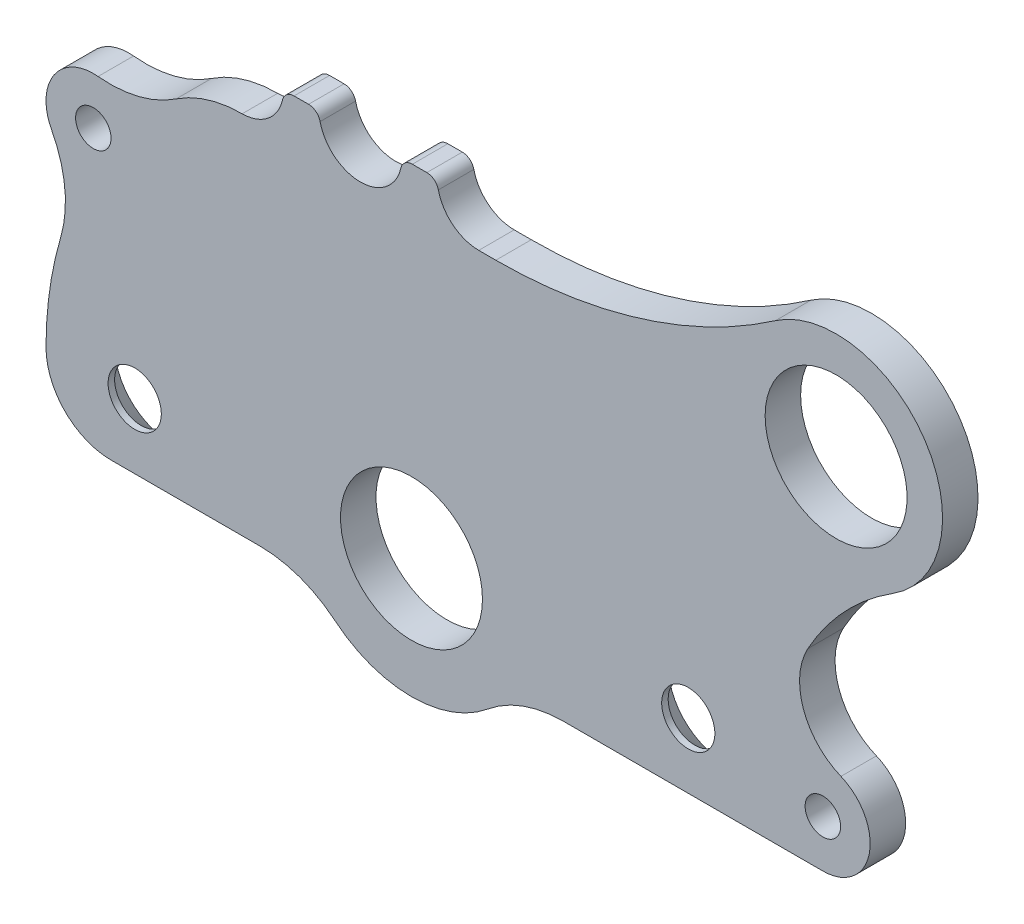
SolidWorks part; units mm, degrees
ref_plane "Front Plane" through (0, 0, 0) normal (0, 0, 1) x (1, 0, 0)
ref_plane "Top Plane" through (0, 0, 0) normal (0, 1, 0) x (1, 0, 0)
ref_plane "Right Plane" through (0, 0, 0) normal (1, 0, 0) x (0, 0, -1)
sketch "Sketch1" plane through (0, 0, 0) normal (0, 0, 1) x (1, 0, 0)
  line L0 (-25.4, 0) -> (25.4, 0) construction
  line L1 (-25.4, 2.5) -> (25.4, 2.5) construction
  line L2 (-25.4, -2.5) -> (25.4, -2.5) construction
  line L3 (-25.4, 0) -> (-21.4, 0) construction
  line L6 (-25.4, 2.5) -> (-21.4, 2.5) construction
  line L7 (-25.4, -2.5) -> (-21.4, -2.5) construction
  line L8 (0, 0) -> (0, -25.4) construction
  line L9 (25.4, 0) -> (21.4, 0) construction
  line L10 (25.4, 2.5) -> (21.4, 2.5) construction
  line L11 (25.4, -2.5) -> (21.4, -2.5) construction
  line L12 (-25.4, 0) -> (25.4, 0) construction
  line L13 (-25.4, 5.5) -> (25.4, 5.5) construction
  line L14 (-25.4, -5.5) -> (25.4, -5.5) construction
  line L17 (-25.4, -5.5) -> (-12.8349, -5.5)
  line L18 (12.8349, -5.5) -> (25.4, -5.5)
  circle A0 centre (0, 0) radius 25.4 construction
  circle A1 centre (0, 0) radius 6.35 construction
  arc A2 (-25.4, 2.5) -> (-25.4, -2.5) centre (-25.4, 0) ccw construction
  arc A3 (25.4, -2.5) -> (25.4, 2.5) centre (25.4, 0) ccw construction
  arc A6 (-25.4, 2.5) -> (-25.4, -2.5) centre (-25.4, 0) ccw construction
  arc A7 (-21.4, -2.5) -> (-21.4, 2.5) centre (-21.4, 0) ccw construction
  arc A8 (25.4, 2.5) -> (25.4, -2.5) centre (25.4, 0) cw construction
  arc A9 (21.4, -2.5) -> (21.4, 2.5) centre (21.4, 0) cw construction
  arc A10 (-25.4, 5.5) -> (-25.4, -5.5) centre (-25.4, 0) ccw construction
  arc A11 (25.4, -5.5) -> (25.4, 5.5) centre (25.4, 0) ccw construction
  arc A12 (-30.9, 0) -> (30.9, 0) centre (0, 0) cw
  arc A14 (-30.9, 0) -> (-25.4, -5.5) centre (-25.4, 0) ccw
  arc A15 (30.9, 0) -> (25.4, -5.5) centre (25.4, 0) cw
  arc A16 (-6.4571, -7.7978) -> (6.4571, -7.7978) centre (0, 0) ccw
  arc A17 (12.8349, -5.5) -> (6.4571, -7.7978) centre (12.8349, -15.5) ccw
  arc A18 (-12.8349, -5.5) -> (-6.4571, -7.7978) centre (-12.8349, -15.5) cw
  circle A19 centre (0, 0) radius 6
  point P6 (0, 0)
  point P13 (-23.4, 0)
  point P21 (23.4, 0)
  point P28 (0, 0)
  point P43 (8.5, -5.5)
  point P47 (-8.5, -5.5)
  dimension "D1" = 50.8
  dimension "D2" = 12.7
  dimension "D5" = 4
  dimension "D6" = 3
  dimension "D7" = 17
  dimension "D8" = 10
  dimension "D9" = 12
  dimension "D3" = 50.8
  dimension "D4" = 5
extrude "Boss-Extrude1" add sketch "Sketch1" along normal mid plane 3
sketch "Sketch2" plane through (0, 0, 1.5) normal (0, 0, 1) x (1, 0, 0)
  line L0 (-30.9, 18.0596) -> (-30.9, 0) construction
  circle A0 centre (-26.9, 18.0596) radius 1.5
  circle A1 centre (-26.9, 18.0596) radius 4
  arc A2 (30.9, 0) -> (-30.9, 0) centre (0, 0) ccw construction
  dimension "D1" = 3
  dimension "D2" = 8
extrude "Boss-Extrude2" add sketch "Sketch2" against normal through all
fillet "Fillet1" radius 10 2 edges at (-23.4635, 20.1066, 0) (-27.4935, 14.1039, 0)
hole_wizard "CSK for M4 Countersunk Flat Head Screw1" positions "Sketch3" profile "Sketch4" countersink size "M4" standard "ISO"
sketch "Sketch3" plane through (0, 0, -1.5) normal (0, 0, -1) x (-1, 0, 0)
  point P9 (-23.4, 0)
  point P12 (23.4, 0)
sketch "Sketch4" plane through (23.4, 0, -1.5) normal (1, 0, 0) x (0, 1, 0)
  line L0 (0, 0) -> (0, 8.8519)
  line L1 (0, 8.8519) -> (2.25, 7.5)
  line L2 (2.25, 7.5) -> (2.25, 2.45)
  line L3 (2.25, 2.45) -> (4.7, 0)
  line L5 (4.7, 0) -> (0, 0)
  line L6 (-2.25, 2.45) -> (-4.7, 0) construction
  line L10 (0, 8.8519) -> (-2.25, 7.5) construction
  line L11 (0, -6.35) -> (0, 107.95) construction
  dimension "Hole Dia." = 4.5
  dimension "Hole Depth" = 7.5
  dimension "Near C'Sink Dia." = 9.4
  dimension "Near C'Sink Angle" = 90
  dimension "Drill Angle" = 118
sketch "Sketch6" plane through (0, 0, 1.5) normal (0, 0, 1) x (1, 0, 0)
  line L0 (-17.5969, 25.4) -> (17.5969, 25.4)
  arc A1 (30.9, 0) -> (-30.9, 0) centre (0, 0) ccw construction
  circle A2 centre (0, 0) radius 25.4 construction
  arc A3 (-17.5969, 25.4) -> (17.5969, 25.4) centre (0, 0) cw
  point P3 (0, 25.4)
extrude "Cut-Extrude1" cut sketch "Sketch6" against normal through all
fillet "Fillet2" radius 10 2 edges at (17.5969, 25.4, 0) (-17.5969, 25.4, 0)
sketch "Sketch7" plane through (0, 0, -1.5) normal (0, 0, -1) x (-1, 0, 0)
  line L0 (-30.9, 38.9) -> (-30.9, 0) construction
  line L1 (-14.1298, 25.4) -> (-35.9, 25.4) construction
  line L2 (14.3137, 25.4) -> (-14.1298, 25.4) construction
  line L3 (-14.1298, 25.4) -> (-7.1298, 25.4)
  circle A0 centre (-21.9, 38.9) radius 6 construction
  arc A2 (-12.9, 38.9) -> (-30.9, 38.9) centre (-21.9, 38.9) ccw construction
  arc A4 (-14.1298, 25.4) -> (-20.8904, 22.7684) centre (-14.1298, 15.4) ccw construction
  arc A6 (-20.8904, 22.7684) -> (-30.9, 0) centre (0, 0) ccw construction
  arc A7 (-14.1298, 25.4) -> (-20.8904, 22.7684) centre (-14.1298, 15.4) ccw
  arc A8 (-20.8904, 22.7684) -> (-30.9, 0) centre (0, 0) ccw
  arc A9 (-12.9, 38.9) -> (-7.1298, 25.4) centre (5.7773, 38.9) ccw construction
  circle A10 centre (-35.9, 25.4) radius 6
  arc A11 (-30.7711, 32.7956) -> (-40.7058, 17.7905) centre (-35.9, 25.4) ccw
  arc A12 (-7.1298, 25.4) -> (-30.7711, 32.7956) centre (-7.1298, 66.8848) cw
  arc A13 (-40.7058, 17.7905) -> (-30.9, 0) centre (-51.9414, 0) cw
  circle A14 centre (-35.9, 25.4) radius 9 construction
  dimension "D1" = 12
  dimension "D2" = 13.5
  dimension "D3" = 3
  dimension "D4" = 7
  dimension "D6" = 5
  dimension "D5" = 3
extrude "Boss-Extrude6" add sketch "Sketch7" against normal through all
sketch "Sketch10" plane through (0, 0, -1.5) normal (0, 0, -1) x (-1, 0, 0)
  line L0 (-34.7808, -5.5) -> (-25.4, -5.5)
  circle A0 centre (-34.7808, -1.5) radius 1.5
  arc A1 (-36.3083, 2.1969) -> (-34.7808, -5.5) centre (-34.7808, -1.5) ccw
  circle A2 centre (26.9, 18.0596) radius 1.5 construction
  arc A3 (-36.3083, 2.1969) -> (-33.5138, 10.157) centre (-38.4687, 7.4259) ccw
  arc A4 (-30.9, 0) -> (-40.7058, 17.7905) centre (-51.9414, 0) ccw construction
  arc A5 (-30.9, 0) -> (-25.4, -5.5) centre (-25.4, 0) ccw construction
  arc A6 (-30.9, 0) -> (-25.4, -5.5) centre (-25.4, 0) ccw
  arc A7 (-30.9, 0) -> (-33.5138, 10.157) centre (-51.9414, 0) ccw
  dimension "D1" = 8
extrude "Boss-Extrude7" add sketch "Sketch10" against normal through all
sketch "Sketch11" plane through (0, 0, -1.5) normal (0, 0, -1) x (-1, 0, 0)
  line L0 (14.3137, 25.4) -> (-7.1298, 25.4) construction
  line L1 (14.3137, 25.4) -> (-1.6059, 25.4)
  arc A0 (-1.6059, 25.4) -> (25.3666, 21.9888) centre (13.3607, 35.4) ccw
  arc A1 (30.4304, 16.1791) -> (26.4962, 22.0392) centre (26.9, 18.0596) ccw construction
  arc A2 (19.9002, 23.6941) -> (26.4962, 22.0392) centre (25.4867, 31.9881) ccw construction
  arc A3 (19.9002, 23.6941) -> (14.3137, 25.4) centre (14.3137, 15.4) ccw construction
  arc A4 (19.9002, 23.6941) -> (25.3666, 21.9888) centre (25.4867, 31.9881) ccw
  arc A5 (19.9002, 23.6941) -> (14.3137, 25.4) centre (14.3137, 15.4) ccw
  dimension "D1" = 36
  dimension "D2" = 8
sketch "Sketch12" plane through (0, 0, -1.5) normal (0, 0, -1) x (-1, 0, 0)
  line L0 (14.3137, 25.4) -> (-1.6059, 25.4) construction
  line L1 (0.8137, 28.9) -> (7.8137, 28.9) construction
  line L2 (0.8137, 28.9) -> (-2.1863, 28.9)
  line L3 (7.8137, 28.9) -> (10.8137, 28.9)
  line L4 (14.3137, 25.4) -> (-7.1298, 25.4) construction
  line L5 (14.3137, 25.4) -> (-5.6863, 25.4)
  arc A0 (0.8137, 28.9) -> (7.8137, 28.9) centre (4.3137, 28.9) ccw
  arc A1 (-2.1863, 28.9) -> (-1.1635, 25.4) centre (4.3137, 28.9) ccw construction
  arc A2 (0.8137, 28.9) -> (7.8137, 28.9) centre (4.3137, 28.9) ccw construction
  arc A3 (10.8137, 28.9) -> (14.3137, 25.4) centre (14.3137, 28.9) ccw
  arc A4 (19.9002, 23.6941) -> (14.3137, 25.4) centre (14.3137, 15.4) ccw construction
  arc A5 (-2.1863, 28.9) -> (-5.6863, 25.4) centre (-5.6863, 28.9) cw
  arc A6 (9.791, 25.4) -> (10.8137, 28.9) centre (4.3137, 28.9) ccw construction
  arc A7 (-2.1863, 28.9) -> (10.8137, 28.9) centre (4.3137, 28.9) ccw construction
  line M6 (14.3137, 25.4) -> (-7.1298, 25.4)
  dimension "D2" = 7
  dimension "D1" = 3
extrude "Boss-Extrude8" add sketch "Sketch12" against normal through all contours A3 L3 A0 M6 | L2 A5 L5 A0
fillet "Fillet3" radius 1 4 edges at (-10.8137, 28.9, 0) (-7.8137, 28.9, 0) (-0.8137, 28.9, 0) (2.1863, 28.9, 0)
